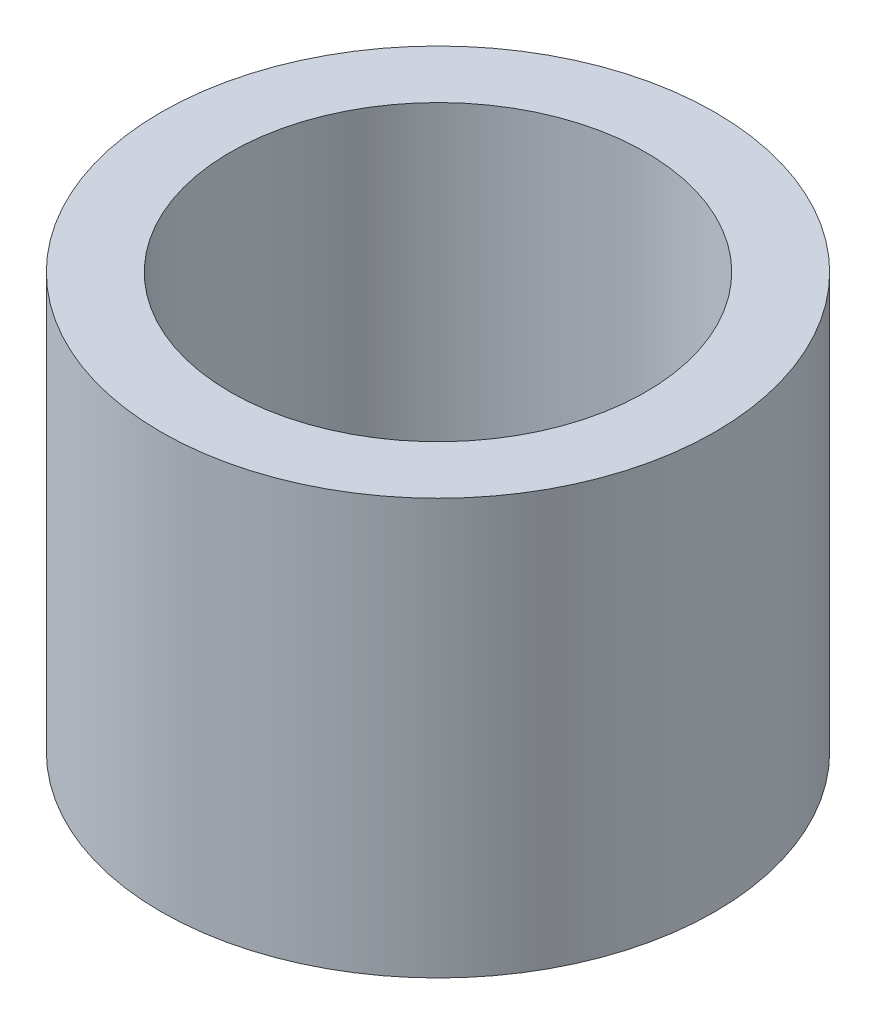
SolidWorks part; units mm, degrees
ref_plane "Front Plane" through (0, 0, 0) normal (0, 0, 1) x (1, 0, 0)
ref_plane "Top Plane" through (0, 0, 0) normal (0, 1, 0) x (1, 0, 0)
ref_plane "Right Plane" through (0, 0, 0) normal (1, 0, 0) x (0, 0, -1)
sketch "Sketch1" plane through (0, 0, 0) normal (0, 1, 0) x (1, 0, 0)
  circle A0 centre (0, 0) radius 3
  circle A1 centre (0, 0) radius 4
  dimension "D1" = 6
  dimension "D2" = 1
extrude "Boss-Extrude1" add sketch "Sketch1" along normal blind 6
